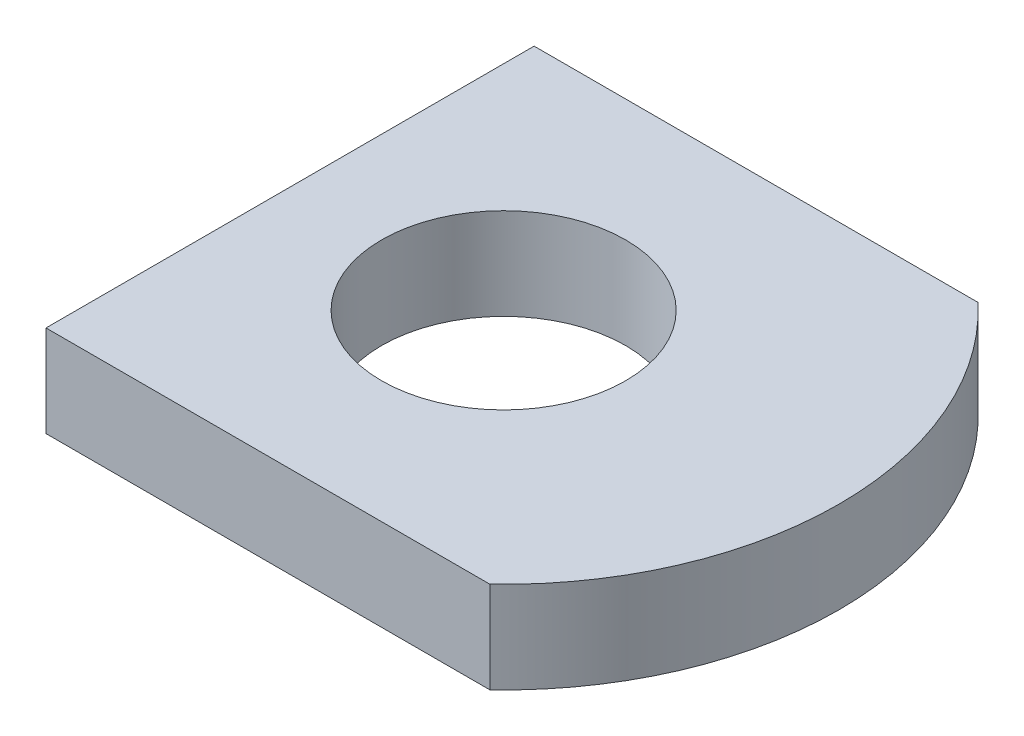
SolidWorks part; units mm, degrees
ref_plane "Alzado" through (0, 0, 0) normal (0, 0, 1) x (1, 0, 0)
ref_plane "Planta" through (0, 0, 0) normal (0, 1, 0) x (1, 0, 0)
ref_plane "Vista lateral" through (0, 0, 0) normal (1, 0, 0) x (0, 0, -1)
sketch "Croquis1" plane through (0, 0, 0) normal (0, 1, 0) x (1, 0, 0)
  line L1 (0, 0) -> (14.5498, 0)
  line L2 (0, 0) -> (0, 16)
  line L3 (0, 16) -> (14.5498, 16)
  circle A0 centre (7, 8) radius 4
  arc A1 (14.5498, 0) -> (14.5498, 16) centre (7, 8) ccw
  dimension "D3" = 8
  dimension "D2" = 11
  dimension "D1" = 16
  dimension "D4" = 7
  dimension "D5" = 8
extrude "Saliente-Extruir1" add sketch "Croquis1" along normal blind 3
